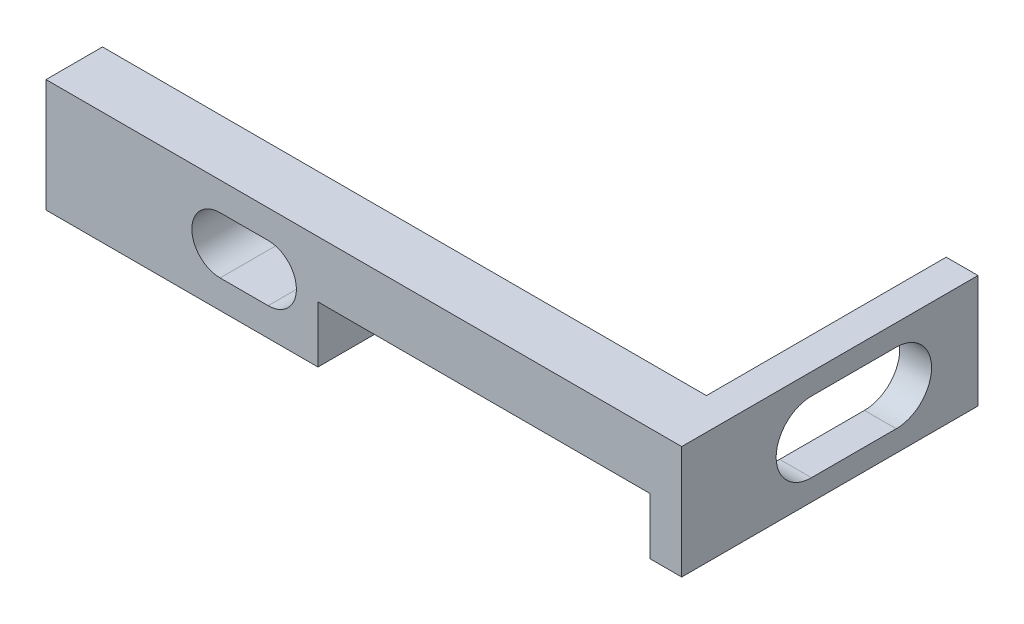
SolidWorks part; units mm, degrees
ref_plane "Front Plane" through (0, 0, 0) normal (0, 0, 1) x (1, 0, 0)
ref_plane "Top Plane" through (0, 0, 0) normal (0, 1, 0) x (1, 0, 0)
ref_plane "Right Plane" through (0, 0, 0) normal (1, 0, 0) x (0, 0, -1)
sketch "Sketch1" plane through (0, 0, 0) normal (0, 1, 0) x (1, 0, 0)
  line L1 (-22.5, 12.5) -> (22.5, 12.5)
  line L2 (-22.5, 12.5) -> (-22.5, -12.5)
  line L3 (-22.5, -12.5) -> (22.5, -12.5)
  line L4 (22.5, 12.5) -> (22.5, -12.5)
  line L5 (-22.5, 12.5) -> (22.5, -12.5) construction
  line L6 (-22.5, -12.5) -> (22.5, 12.5) construction
  point P0 (0, 0)
  dimension "D1" = 45
  dimension "D2" = 25
extrude "Boss-Extrude1" add sketch "Sketch1" along normal blind 4
sketch "Sketch5" plane through (0, 4, 0) normal (0, 1, 0) x (1, 0, 0)
  line L1 (-20.25, 8.5) -> (20.25, 8.5)
  line L2 (-20.25, 8.5) -> (-20.25, -8.5)
  line L3 (-20.25, -8.5) -> (20.25, -8.5)
  line L4 (20.25, 8.5) -> (20.25, -8.5)
  line L5 (-20.25, 8.5) -> (20.25, -8.5) construction
  line L6 (-20.25, -8.5) -> (20.25, 8.5) construction
  point P0 (0, 0)
  dimension "D1" = 17
  dimension "D2" = 40.5
extrude "Cut-Extrude2" cut sketch "Sketch5" against normal through all
sketch "Sketch6" plane through (0, 4, 0) normal (0, 1, 0) x (1, 0, 0)
  line L0 (22.5, -12.5) -> (22.5, 12.5) construction
  line L1 (-22.5, 12.5) -> (22.5, 12.5)
  line L2 (-22.5, 12.5) -> (-22.5, 8.4747)
  line L3 (-22.5, 8.4747) -> (22.5, 8.4747)
  line L4 (22.5, 12.5) -> (22.5, 8.4747)
extrude "Cut-Extrude3" cut sketch "Sketch6" against normal through all
sketch "Sketch13" plane through (0, 4, 0) normal (0, 1, 0) x (1, 0, 0)
  line L2 (20.25, 8.4747) -> (22.5, 8.4747)
  line L3 (20.25, 8.4747) -> (20.25, -12.5)
  line L4 (20.25, -12.5) -> (22.5, -12.5)
  line L5 (22.5, 8.4747) -> (22.5, -12.5)
extrude "Boss-Extrude3" add sketch "Sketch13" against normal blind 8
sketch "Sketch16" plane through (0, 4, 0) normal (0, 1, 0) x (1, 0, 0)
  line L1 (-22.5, -12.5) -> (-20.25, -12.5)
  line L2 (-22.5, -12.5) -> (-22.5, 8.4747)
  line L3 (-22.5, 8.4747) -> (-20.25, 8.4747)
  line L4 (-20.25, -12.5) -> (-20.25, 8.4747)
extrude "Boss-Extrude4" add sketch "Sketch16" against normal blind 8
sketch "Sketch19" plane through (0, 0, 0) normal (0, -1, 0) x (1, 0, 0)
  line L0 (-20.25, 8.5) -> (20.25, 8.5) construction
  line L1 (20.25, 12.5) -> (3.25, 12.5)
  line L2 (20.25, 12.5) -> (20.25, 8.5)
  line L3 (20.25, 8.5) -> (3.25, 8.5)
  line L4 (3.25, 12.5) -> (3.25, 8.5)
  dimension "D1" = 17
extrude "Boss-Extrude5" add sketch "Sketch19" along normal blind 4
sketch "Sketch21" plane through (0, 4, 0) normal (0, 1, 0) x (1, 0, 0)
  line L1 (20.25, -8.5) -> (22.5, -8.5)
  line L2 (20.25, -8.5) -> (20.25, 8.4747)
  line L3 (20.25, 8.4747) -> (22.5, 8.4747)
  line L4 (22.5, -8.5) -> (22.5, 8.4747)
extrude "Cut-Extrude7" cut sketch "Sketch21" against normal through all
sketch "Sketch25" plane through (-22.5, 0, 0) normal (-1, 0, 0) x (0, 0, 1)
  line L0 (3.3145, 0) -> (-2.6855, 0) construction
  line L1 (3.3145, -2.5) -> (-2.6855, -2.5)
  line L2 (3.3145, 2.5) -> (-2.6855, 2.5)
  arc A0 (3.3145, -2.5) -> (3.3145, 2.5) centre (3.3145, 0) ccw
  arc A1 (-2.6855, 2.5) -> (-2.6855, -2.5) centre (-2.6855, 0) ccw
  point P3 (0.3145, 0)
  dimension "D1" = 3
  dimension "D2" = 2.5
extrude "Cut-Extrude9" cut sketch "Sketch25" against normal through all
sketch "Sketch26" plane through (0, 0, 12.5) normal (0, 0, 1) x (1, 0, 0)
  line L1 (-20.25, 0) -> (5.75, 0)
  line L2 (-20.25, 0) -> (-20.25, -3.7687)
  line L3 (-20.25, -3.7687) -> (5.75, -3.7687)
  line L4 (5.75, 0) -> (5.75, -3.7687)
  point P5 (0, 0)
  dimension "D1" = 26
sketch "Sketch29" plane through (0, 0, 12.5) normal (0, 0, 1) x (1, 0, 0)
  line L0 (6.7748, 0) -> (10.1748, 0) construction
  line L1 (6.7748, 2) -> (10.1748, 2)
  line L2 (6.7748, -2) -> (10.1748, -2)
  arc A0 (6.7748, 2) -> (6.7748, -2) centre (6.7748, 0) ccw
  arc A1 (10.1748, -2) -> (10.1748, 2) centre (10.1748, 0) ccw
  point P4 (8.4748, 0)
  point P9 (0, 0)
  point P10 (9.6067, 0)
  point P11 (8.0379, 0)
  point P12 (0, 0)
  point P13 (10.4297, 0)
  point P14 (8.4748, 0)
  dimension "D1" = 1.7
  dimension "D2" = 2
extrude "Cut-Extrude14" cut sketch "Sketch29" against normal through all
mirror "Mirror1" about plane through (22.5, 4, -12.5) normal (-1, 0, 0) of bodies 120
delete or keep bodies "Body-Delete/Keep 1" type delete bodies bodies 120
